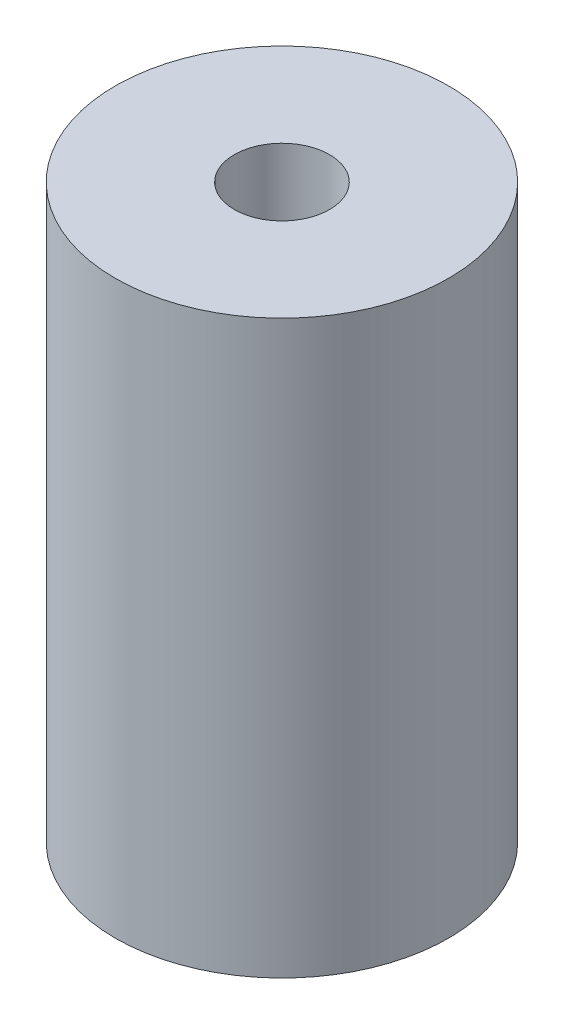
SolidWorks part; units mm, degrees
ref_plane "Front Plane" through (0, 0, 0) normal (0, 0, 1) x (1, 0, 0)
ref_plane "Top Plane" through (0, 0, 0) normal (0, 1, 0) x (1, 0, 0)
ref_plane "Right Plane" through (0, 0, 0) normal (1, 0, 0) x (0, 0, -1)
sketch "Sketch1" plane through (0, 0, 0) normal (0, 1, 0) x (1, 0, 0)
  circle A0 centre (0, 0) radius 3.5
  circle A1 centre (0, 0) radius 1
  dimension "D1" = 2
  dimension "D2" = 7
extrude "Boss-Extrude1" add sketch "Sketch1" along normal blind 12
